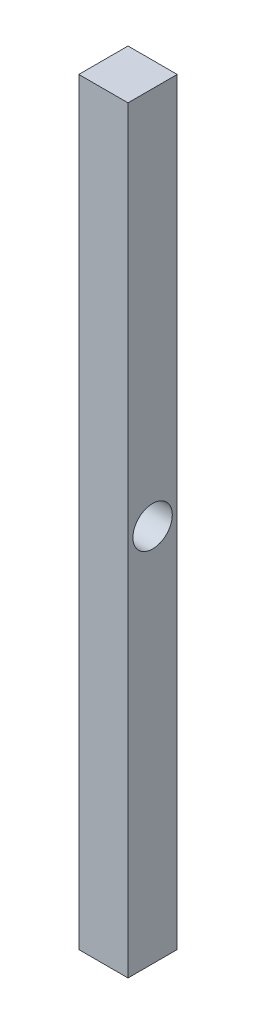
SolidWorks part; units mm, degrees
ref_plane "Front Plane" through (0, 0, 0) normal (0, 0, 1) x (1, 0, 0)
ref_plane "Top Plane" through (0, 0, 0) normal (0, 1, 0) x (1, 0, 0)
ref_plane "Right Plane" through (0, 0, 0) normal (1, 0, 0) x (0, 0, -1)
sketch "Sketch1" plane through (0, 0, 0) normal (0, 1, 0) x (1, 0, 0)
  line L1 (-5, 5) -> (5, 5)
  line L2 (-5, 5) -> (-5, -5)
  line L3 (-5, -5) -> (5, -5)
  line L4 (5, 5) -> (5, -5)
  line L5 (-5, 5) -> (5, -5) construction
  line L6 (-5, -5) -> (5, 5) construction
  point P0 (0, 0)
  dimension "D1" = 10
  dimension "D2" = 10
extrude "Boss-Extrude1" add sketch "Sketch1" along normal blind 154
sketch "Sketch2" plane through (5, 0, 0) normal (1, 0, 0) x (0, 0, -1)
  line L0 (0, 154) -> (0, 0) construction
  line L1 (-5, 154) -> (5, 154) construction
  circle A0 centre (0, 77) radius 4
  dimension "D1" = 8
extrude "Cut-Extrude1" cut sketch "Sketch2" against normal through all both and the other way through all
